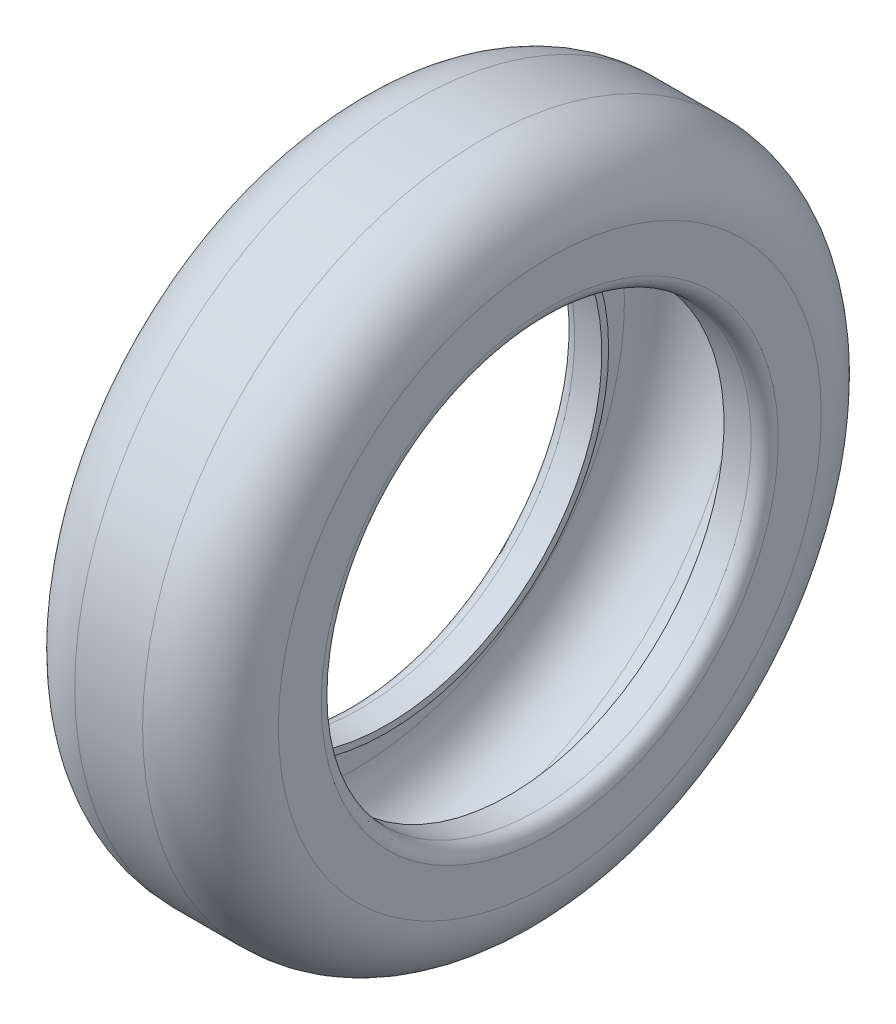
SolidWorks part; units mm, degrees
ref_plane "Front Plane" through (0, 0, 0) normal (0, 0, 1) x (1, 0, 0)
ref_plane "Top Plane" through (0, 0, 0) normal (0, 1, 0) x (1, 0, 0)
ref_plane "Right Plane" through (0, 0, 0) normal (1, 0, 0) x (0, 0, -1)
sketch "Sketch2" plane through (0, 0, 0) normal (0, 0, 1) x (1, 0, 0)
  line L0 (-45, 0) -> (45, 0) construction
  line L1 (-45, 0) -> (-45, 158.3485) construction
  line L2 (-45, 158.3485) -> (-65, 158.3485)
  line L3 (-75, 168.3485) -> (-75, 200)
  line L4 (-25, 250) -> (25, 250)
  line L5 (75, 200) -> (75, 168.3485)
  line L6 (65, 158.3485) -> (45, 158.3485)
  line L7 (45, 158.3485) -> (45, 0) construction
  line L8 (-45, 163.3485) -> (-65, 163.3485)
  line L9 (-70, 168.3485) -> (-70, 200)
  line L10 (-25, 245) -> (25, 245)
  line L11 (70, 200) -> (70, 168.3485)
  line L12 (65, 163.3485) -> (45, 163.3485)
  line L13 (-45, 163.3485) -> (-45, 158.3485)
  line L14 (45, 163.3485) -> (45, 158.3485)
  arc A0 (25, 250) -> (75, 200) centre (25, 200) cw
  arc A1 (-75, 200) -> (-25, 250) centre (-25, 200) cw
  arc A2 (75, 168.3485) -> (65, 158.3485) centre (65, 168.3485) cw
  arc A3 (-65, 158.3485) -> (-75, 168.3485) centre (-65, 168.3485) cw
  arc A4 (-65, 163.3485) -> (-70, 168.3485) centre (-65, 168.3485) cw
  arc A5 (-70, 200) -> (-25, 245) centre (-25, 200) cw
  arc A6 (25, 245) -> (70, 200) centre (25, 200) cw
  arc A7 (70, 168.3485) -> (65, 163.3485) centre (65, 168.3485) cw
  point P4 (0, 0)
  dimension "D1" = 50
  dimension "D2" = 10
  dimension "D3" = 150
  dimension "D4" = 250
  dimension "D5" = 20
  dimension "D6" = 20
  dimension "D7" = 100
  dimension "D8" = 50
  dimension "D9" = 5
revolve "Revolve2" add sketch "Sketch2" angle 360 about L0
sketch "Sketch3" plane through (0, 0, 0) normal (0, 0, 1) x (1, 0, 0)
  line L0 (-25, 250) -> (-25, 245)
  line L1 (-20, 250) -> (-10, 250)
  line L2 (-20, 250) -> (-20, 247)
  line L3 (-20, 247) -> (-10, 247)
  line L4 (-10, 250) -> (-10, 247)
  line L5 (-5, 250) -> (5, 250)
  line L6 (-5, 250) -> (-5, 247)
  line L7 (-5, 247) -> (5, 247)
  line L8 (5, 250) -> (5, 247)
  line L9 (10, 250) -> (20, 250)
  line L10 (10, 250) -> (10, 247)
  line L11 (10, 247) -> (20, 247)
  line L12 (-65, 158.3485) -> (-45, 158.3485)
  line L13 (-45, 158.3485) -> (-45, 163.3485)
  line L14 (-45, 163.3485) -> (-65, 163.3485)
  line L15 (-70, 168.3485) -> (-70, 200)
  line L16 (-25, 245) -> (25, 245)
  line L17 (70, 200) -> (70, 168.3485)
  line L18 (65, 163.3485) -> (45, 163.3485)
  line L19 (45, 163.3485) -> (45, 158.3485)
  line L20 (45, 158.3485) -> (65, 158.3485)
  line L21 (75, 168.3485) -> (75, 200)
  line L22 (25, 250) -> (-25, 250)
  line L23 (-75, 200) -> (-75, 168.3485)
  line L24 (-65, 158.3485) -> (-45, 158.3485)
  line L25 (-45, 158.3485) -> (-45, 163.3485)
  line L26 (-45, 163.3485) -> (-65, 163.3485)
  line L27 (-70, 168.3485) -> (-70, 200)
  line L28 (-25, 245) -> (25, 245)
  line L29 (70, 200) -> (70, 168.3485)
  line L30 (65, 163.3485) -> (45, 163.3485)
  line L31 (45, 163.3485) -> (45, 158.3485)
  line L32 (45, 158.3485) -> (65, 158.3485)
  line L33 (75, 168.3485) -> (75, 200)
  line L34 (25, 250) -> (-25, 250)
  line L35 (-75, 200) -> (-75, 168.3485)
  line L36 (20, 250) -> (20, 247)
  line L37 (25, 245) -> (25, 250)
  line L38 (-25, 245) -> (-25, 242)
  line L39 (-25, 250) -> (-25, -250) construction
  line L40 (-25, 242) -> (25, 242)
  line L41 (25, 250) -> (25, -250) construction
  arc A8 (-70, 168.3485) -> (-65, 163.3485) centre (-65, 168.3485) ccw
  arc A9 (-25, 245) -> (-70, 200) centre (-25, 200) ccw
  arc A10 (70, 200) -> (25, 245) centre (25, 200) ccw
  arc A11 (65, 163.3485) -> (70, 168.3485) centre (65, 168.3485) ccw
  arc A12 (65, 158.3485) -> (75, 168.3485) centre (65, 168.3485) ccw
  arc A13 (75, 200) -> (25, 250) centre (25, 200) ccw
  arc A14 (-25, 250) -> (-75, 200) centre (-25, 200) ccw
  arc A15 (-75, 168.3485) -> (-65, 158.3485) centre (-65, 168.3485) ccw
  arc A16 (-70, 168.3485) -> (-65, 163.3485) centre (-65, 168.3485) ccw
  arc A17 (-25, 245) -> (-70, 200) centre (-25, 200) ccw
  arc A18 (70, 200) -> (25, 245) centre (25, 200) ccw
  arc A19 (65, 163.3485) -> (70, 168.3485) centre (65, 168.3485) ccw
  arc A20 (65, 158.3485) -> (75, 168.3485) centre (65, 168.3485) ccw
  arc A21 (75, 200) -> (25, 250) centre (25, 200) ccw
  arc A22 (-25, 250) -> (-75, 200) centre (-25, 200) ccw
  arc A23 (-75, 168.3485) -> (-65, 158.3485) centre (-65, 168.3485) ccw
  dimension "D2" = 3
  dimension "D3" = 10
  dimension "D4" = 10
  dimension "D5" = 10
  dimension "D6" = 5
  dimension "D7" = 5
  dimension "D8" = 5
  dimension "D9" = 3
  dimension "D10" = 3
  dimension "D11" = 3
  dimension "D1" = 0
